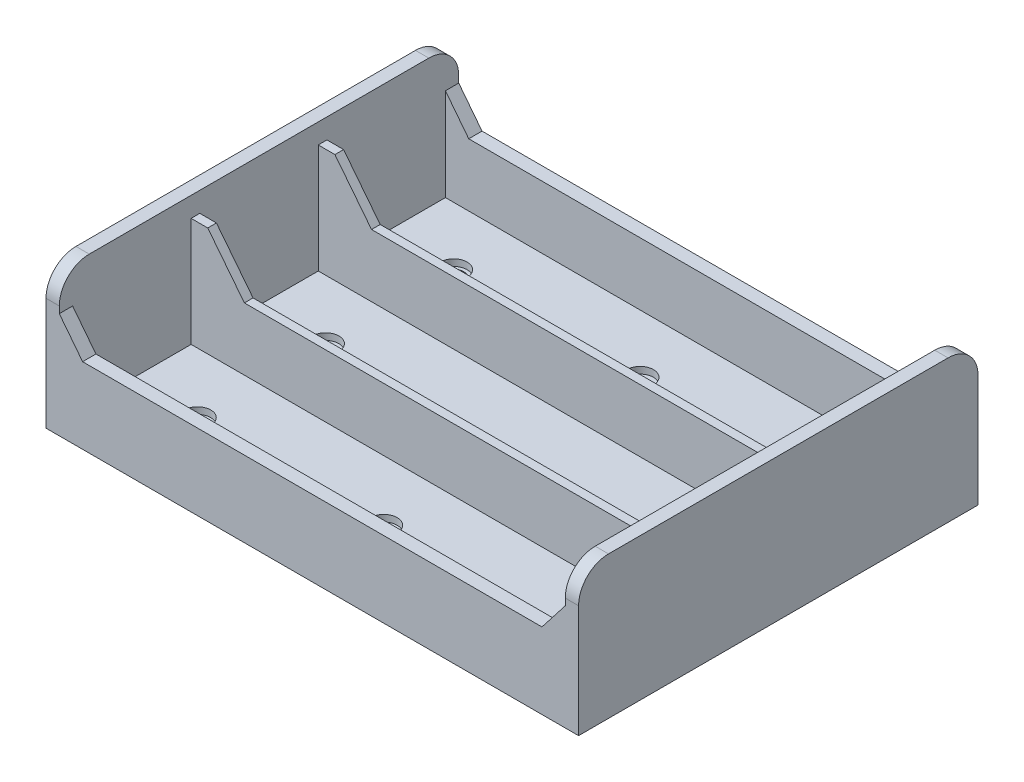
SolidWorks part; units mm, degrees
ref_plane "前视基准面" through (0, 0, 0) normal (0, 0, 1) x (1, 0, 0)
ref_plane "上视基准面" through (0, 0, 0) normal (0, 1, 0) x (1, 0, 0)
ref_plane "右视基准面" through (0, 0, 0) normal (1, 0, 0) x (0, 0, -1)
sketch "草图1" plane through (0, 0, 0) normal (0, 1, 0) x (1, 0, 0)
  line L1 (-37.3246, 19.6411) -> (42.6754, 19.6411)
  line L2 (-37.3246, 19.6411) -> (-37.3246, -40.3589)
  line L3 (-37.3246, -40.3589) -> (42.6754, -40.3589)
  line L4 (42.6754, 19.6411) -> (42.6754, -40.3589)
  dimension "D1" = 80
  dimension "D2" = 60
extrude "凸台-拉伸1" add sketch "草图1" along normal blind 21.4
fillet "圆角1" radius 4.5 2 edges at (2.6754, 21.4, -19.6411) (2.6754, 21.4, 40.3589)
sketch "草图2" plane through (0, 0, 40.3589) normal (0, 0, 1) x (1, 0, 0)
  line L0 (40.6754, 21.4) -> (-35.3246, 21.4)
  line L1 (-37.3246, 21.4) -> (42.6754, 21.4) construction
  line L2 (-35.3246, 21.4) -> (-35.3246, 15.9)
  line L3 (-35.3246, 15.9) -> (-31.8246, 11.4)
  line L4 (-31.8246, 11.4) -> (37.1754, 11.4)
  line L5 (37.1754, 11.4) -> (40.6754, 15.9)
  line L6 (40.6754, 15.9) -> (40.6754, 21.4)
  line L7 (-37.3246, 21.4) -> (-37.3246, 16.9) construction
  line L8 (42.6754, 16.9) -> (42.6754, 21.4) construction
  line L9 (-37.3246, 16.9) -> (-37.3246, 0) construction
  line L10 (42.6754, 16.9) -> (42.6754, 0) construction
  dimension "D1" = 2
  dimension "D2" = 2
  dimension "D3" = 10
  dimension "D4" = 5.5
  dimension "D5" = 5.5
  dimension "D6" = 5.5
extrude "切除-拉伸1" cut sketch "草图2" against normal through all
sketch "草图3" plane through (0, 21.4, 0) normal (0, 1, 0) x (1, 0, 0)
  line L0 (-35.3246, 15.1411) -> (-35.3246, 19.6411) construction
  line L1 (-35.3246, 17.6411) -> (40.6754, 17.6411)
  line L2 (-35.3246, 17.6411) -> (-35.3246, -38.3589)
  line L3 (-35.3246, -38.3589) -> (40.6754, -38.3589)
  line L4 (40.6754, 17.6411) -> (40.6754, -38.3589)
  line L5 (40.6754, 19.6411) -> (40.6754, -40.3589) construction
  line L6 (-35.3246, 19.6411) -> (-31.8246, 19.6411) construction
  line L7 (-35.3246, -40.3589) -> (-31.8246, -40.3589) construction
  dimension "D1" = 2
  dimension "D2" = 2
extrude "切除-拉伸2" cut sketch "草图3" against normal blind 19.4
sketch "草图4" plane through (0, 2, 0) normal (0, 1, 0) x (1, 0, 0)
  line L0 (-35.3246, 15.1411) -> (-35.3246, -35.8589) construction
  line L1 (-35.3246, -0.1589) -> (40.6754, -0.1589)
  line L2 (-35.3246, -0.1589) -> (-35.3246, -1.4589)
  line L3 (-35.3246, -1.4589) -> (40.6754, -1.4589)
  line L4 (40.6754, -0.1589) -> (40.6754, -1.4589)
  line L5 (40.6754, -38.3589) -> (40.6754, 17.6411) construction
  line L6 (-35.3246, 17.6411) -> (-35.3246, -38.3589) construction
  line L7 (-35.3246, -19.2589) -> (40.6754, -19.2589)
  line L8 (-35.3246, -19.2589) -> (-35.3246, -20.5589)
  line L9 (-35.3246, -20.5589) -> (40.6754, -20.5589)
  line L10 (40.6754, -19.2589) -> (40.6754, -20.5589)
  line L11 (40.6754, 15.1411) -> (40.6754, -35.8589) construction
  line L12 (-31.8246, 17.6411) -> (37.1754, 17.6411) construction
  dimension "D1" = 17.8
  dimension "D3" = 17.8
  dimension "D4" = 17.8
extrude "凸台-拉伸2" add sketch "草图4" along normal blind 16.4
sketch "草图5" plane through (0, 0, 20.5589) normal (0, 0, 1) x (1, 0, 0)
  line L0 (-32.825, 18.4) -> (-27.3246, 11.4)
  line L1 (-35.3246, 18.4) -> (40.6754, 18.4) construction
  line L2 (-31.8246, 11.4) -> (37.1754, 11.4) construction
  line L3 (-27.3246, 11.4) -> (32.6754, 11.4)
  line L4 (32.6754, 11.4) -> (38.1754, 18.4)
  line L5 (38.1754, 18.4) -> (-32.825, 18.4)
  line L6 (-37.3246, 21.4) -> (-37.3246, 16.9) construction
  line L7 (42.6754, 16.9) -> (42.6754, 21.4) construction
  line L8 (-37.3246, 16.9) -> (-37.3246, 0) construction
  line L9 (42.6754, 16.9) -> (42.6754, 0) construction
  dimension "D1" = 4.4996
  dimension "D2" = 4.5
  dimension "D3" = 10
  dimension "D4" = 10
extrude "切除-拉伸3" cut sketch "草图5" against normal blind 26.4
sketch "草图6" plane through (0, 2, 0) normal (0, 1, 0) x (1, 0, 0)
  line L0 (-31.8246, 19.6411) -> (37.1754, 19.6411) construction
  line L1 (-37.3246, 19.6411) -> (-37.3246, 15.1411) construction
  line L2 (42.6754, -35.8589) -> (42.6754, 15.1411) construction
  circle A0 centre (2.6754, 8.8911) radius 1.25
  circle A1 centre (2.6754, -29.6089) radius 1.25
  circle A2 centre (-25.3246, 8.8911) radius 1.5
  circle A3 centre (30.6754, 8.8911) radius 1.5
  circle A4 centre (30.6754, -10.8291) radius 1.5
  circle A5 centre (30.6754, -29.6089) radius 1.5
  circle A6 centre (-25.3246, -29.6089) radius 1.5
  circle A7 centre (-25.3246, -10.3589) radius 1.5
  point P27 (2.6754, 19.6411)
  dimension "D1" = 3
  dimension "D3" = 2.5
  dimension "D2" = 38.5
  dimension "D4" = 19.25
  dimension "D5" = 10.75
  dimension "D6" = 12
  dimension "D7" = 12
extrude "切除-拉伸4" cut sketch "草图6" against normal up to next
sketch "草图7" plane through (0, 2, 0) normal (0, 1, 0) x (1, 0, 0)
  circle A1 centre (-25.3246, 8.8911) radius 2
  circle A2 centre (2.6754, 8.8911) radius 2
  circle A3 centre (30.6754, 8.8911) radius 2
  circle A4 centre (-25.3246, -10.3589) radius 2
  circle A5 centre (30.6754, -10.8291) radius 2
  circle A6 centre (-25.3246, -29.6089) radius 2
  circle A7 centre (2.6754, -29.6089) radius 2
  circle A8 centre (30.6754, -29.6089) radius 2
  dimension "D1" = 4
extrude "切除-拉伸5" cut sketch "草图7" against normal blind 1
